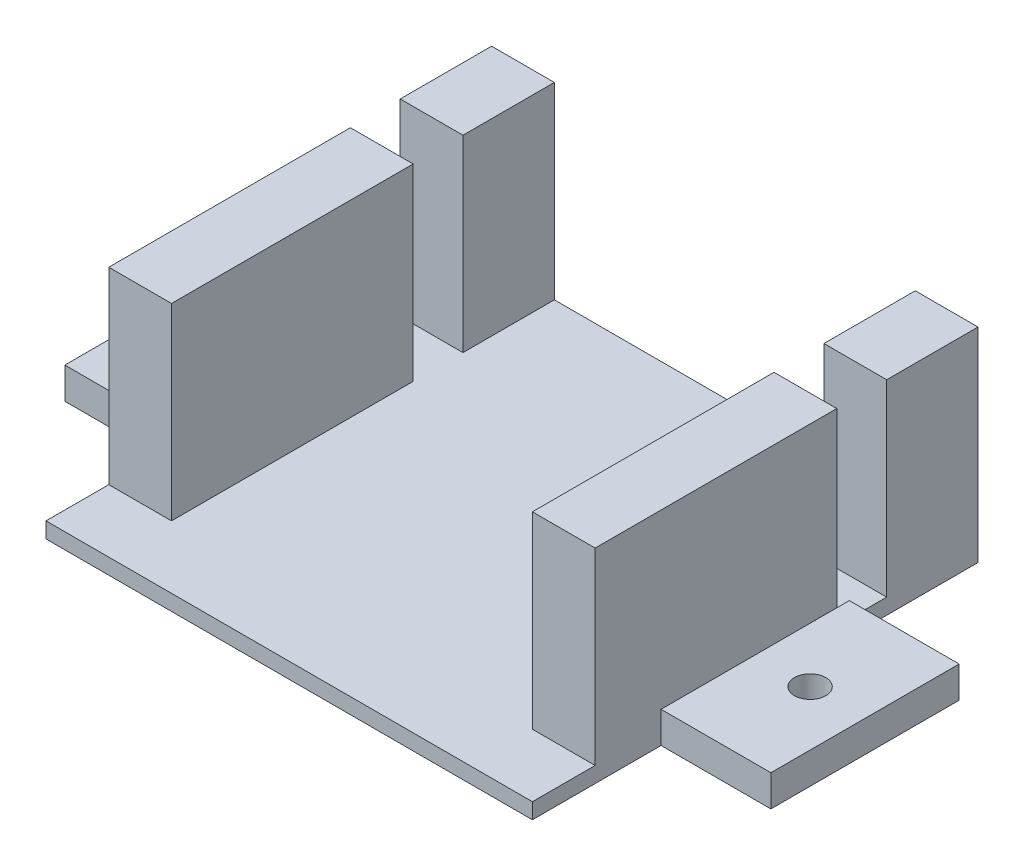
SolidWorks part; units mm, degrees
ref_plane "Front Plane" through (0, 0, 0) normal (0, 0, 1) x (1, 0, 0)
ref_plane "Top Plane" through (0, 0, 0) normal (0, 1, 0) x (1, 0, 0)
ref_plane "Right Plane" through (0, 0, 0) normal (1, 0, 0) x (0, 0, -1)
sketch "Sketch1" plane through (0, 0, 0) normal (0, 1, 0) x (1, 0, 0)
  line L1 (-15.5, -14.2) -> (15.5, -14.2)
  line L2 (-15.5, -14.2) -> (-15.5, 14.2)
  line L3 (-15.5, 14.2) -> (15.5, 14.2)
  line L4 (15.5, -14.2) -> (15.5, 14.2)
  line L5 (-15.5, -14.2) -> (15.5, 14.2) construction
  line L6 (-15.5, 14.2) -> (15.5, -14.2) construction
  point P0 (0, 0)
  dimension "D1" = 31
  dimension "D2" = 28.4
extrude "Boss-Extrude1" add sketch "Sketch1" along normal blind 1
sketch "Sketch3" plane through (0, 1, 0) normal (0, 1, 0) x (1, 0, 0)
  line L1 (-15.5, -14.2) -> (-11.5, -14.2)
  line L2 (-15.5, -14.2) -> (-15.5, 5.2)
  line L3 (-15.5, 5.2) -> (-11.5, 5.2)
  line L4 (-11.5, -14.2) -> (-11.5, 5.2)
  line L5 (15.5, -14.2) -> (11.5, -14.2)
  line L6 (15.5, -14.2) -> (15.5, 5.2)
  line L7 (15.5, 5.2) -> (11.5, 5.2)
  line L8 (11.5, -14.2) -> (11.5, 5.2)
  line L9 (-15.5, 14.2) -> (-11.5, 14.2)
  line L10 (-15.5, 14.2) -> (-15.5, 8.375)
  line L11 (-15.5, 8.375) -> (-11.5, 8.375)
  line L12 (-11.5, 14.2) -> (-11.5, 8.375)
  line L13 (15.5, 14.2) -> (11.5, 14.2)
  line L14 (15.5, 14.2) -> (15.5, 8.38)
  line L15 (15.5, 8.38) -> (11.5, 8.38)
  line L16 (11.5, 14.2) -> (11.5, 8.38)
  dimension "D1" = 4
  dimension "D2" = 19.4
  dimension "D3" = 4
  dimension "D4" = 19.4
  dimension "D5" = 3.175
  dimension "D6" = 3.18
  dimension "D7" = 4
  dimension "D8" = 4
extrude "Boss-Extrude2" add sketch "Sketch3" along normal blind 12
sketch "Sketch4" plane through (0, 13, 0) normal (0, 1, 0) x (1, 0, 0)
  line L0 (-15.5, 5.2) -> (-15.5, -14.2) construction
  line L1 (-15.5, -10.2) -> (15.5, -10.2)
  line L2 (-15.5, -10.2) -> (-15.5, -14.2)
  line L3 (-15.5, -14.2) -> (15.5, -14.2)
  line L4 (15.5, -10.2) -> (15.5, -14.2)
  dimension "D1" = 4
extrude "Cut-Extrude1" cut sketch "Sketch4" against normal up to surface (12 mm away) up to face at (0, 1, -4.5258)
sketch "Sketch7" plane through (0, 0, 0) normal (0, 1, 0) x (1, 0, 0)
  line L0 (15.5, -10.2) -> (15.5, 5.2) construction
  line L1 (15.5, 6) -> (22.5, 6)
  line L2 (15.5, 6) -> (15.5, -6)
  line L3 (15.5, -6) -> (22.5, -6)
  line L4 (22.5, 6) -> (22.5, -6)
  line L5 (-15.5, 5.2) -> (-15.5, -10.2) construction
  line L6 (-15.5, 6) -> (-22.5, 6)
  line L7 (-15.5, 6) -> (-15.5, -6)
  line L8 (-15.5, -6) -> (-22.5, -6)
  line L9 (-22.5, 6) -> (-22.5, -6)
  point P7 (22.5, 0)
  point P15 (-15.5, 0)
  dimension "D1" = 7
  dimension "D2" = 12
  dimension "D3" = 7
  dimension "D4" = 12
extrude "Boss-Extrude3" add sketch "Sketch7" along normal blind 2
sketch "Sketch8" plane through (0, 2, 0) normal (0, 1, 0) x (1, 0, 0)
  line L0 (0, 0) -> (0, 14.9256) construction
  line L1 (-22.5, 6) -> (-22.5, -6) construction
  line L2 (-15.5, 6) -> (-22.5, 6) construction
  circle A0 centre (-19, 0) radius 1
  circle A1 centre (19, 0) radius 1
  dimension "D1" = 2
  dimension "D2" = 3.5
  dimension "D3" = 6
extrude "Cut-Extrude4" cut sketch "Sketch8" against normal through all
